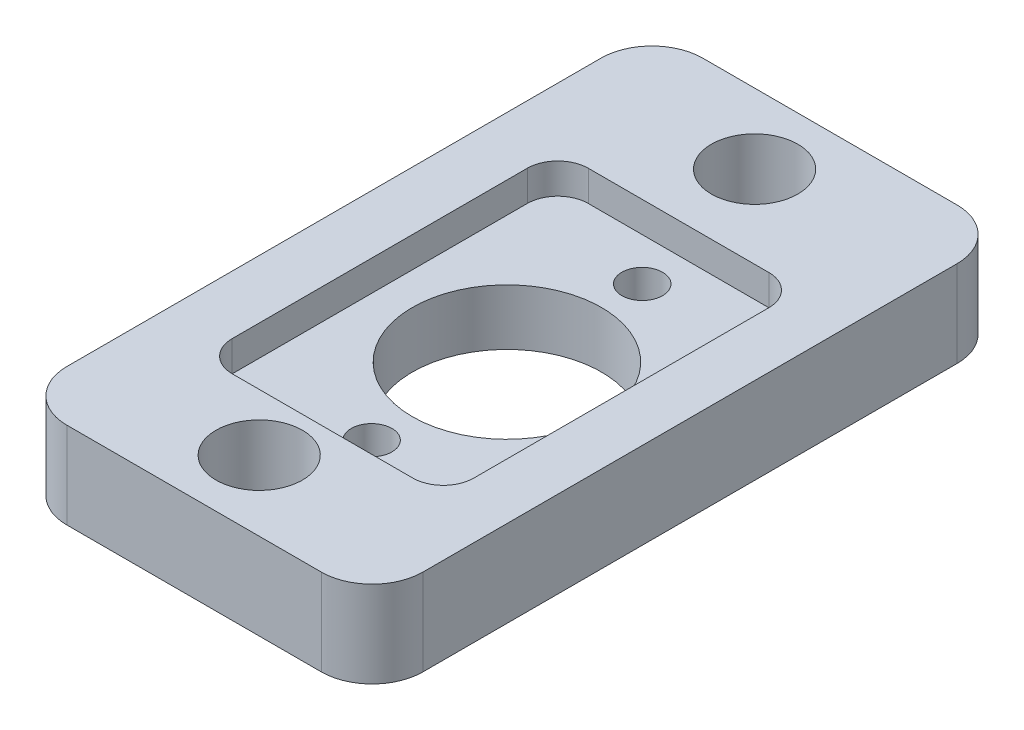
SolidWorks part; units mm, degrees
ref_plane "Front Plane" through (0, 0, 0) normal (0, 0, 1) x (1, 0, 0)
ref_plane "Top Plane" through (0, 0, 0) normal (0, 1, 0) x (1, 0, 0)
ref_plane "Right Plane" through (0, 0, 0) normal (1, 0, 0) x (0, 0, -1)
sketch "Sketch1" plane through (0, 0, 0) normal (0, 1, 0) x (1, 0, 0)
  line L1 (2, 0) -> (12, 0)
  line L2 (0, -2) -> (0, -23)
  line L3 (2, -25) -> (12, -25)
  line L4 (14, -2) -> (14, -23)
  arc A0 (0, -23) -> (2, -25) centre (2, -23) ccw
  arc A1 (12, -25) -> (14, -23) centre (12, -23) ccw
  arc A2 (12, 0) -> (14, -2) centre (12, -2) cw
  arc A3 (2, 0) -> (0, -2) centre (2, -2) ccw
  point P7 (0, -25)
  point P12 (14, 0)
  point P15 (0, 0)
  dimension "D3" = 2
  dimension "D1" = 14
  dimension "D2" = 25
extrude "Boss-Extrude1" add sketch "Sketch1" along normal blind 3.4
sketch "Sketch2" plane through (0, 3.4, 0) normal (0, 1, 0) x (1, 0, 0)
  line L0 (12, 0) -> (2, 0) construction
  line L1 (3.5, -6) -> (10.6, -6)
  line L2 (2.3, -7.2) -> (2.3, -18.8)
  line L3 (3.5, -20) -> (10.6, -20)
  line L4 (11.8, -7.2) -> (11.8, -18.8)
  line L5 (14, -23) -> (14, -2) construction
  arc A0 (2.3, -18.8) -> (3.5, -20) centre (3.5, -18.8) ccw
  arc A1 (10.6, -20) -> (11.8, -18.8) centre (10.6, -18.8) ccw
  arc A2 (10.6, -6) -> (11.8, -7.2) centre (10.6, -7.2) cw
  arc A3 (3.5, -6) -> (2.3, -7.2) centre (3.5, -7.2) ccw
  point P4 (7.05, -6)
  point P9 (2.3, -20)
  point P14 (11.8, -6)
  point P17 (2.3, -6)
  dimension "D4" = 1.2
  dimension "D1" = 9.5
  dimension "D2" = 14
  dimension "D3" = 6
  dimension "D5" = 2.2
extrude "Cut-Extrude1" cut sketch "Sketch2" against normal blind 1.2
sketch "Sketch3" plane through (0, 2.2, 0) normal (0, 1, 0) x (1, 0, 0)
  line L0 (11.8, -18.8) -> (11.8, -7.2) construction
  line L2 (3.5, -20) -> (10.6, -20) construction
  circle A0 centre (7.3, -13) radius 3.72
  circle A1 centre (7.3, -7.68) radius 0.8
  circle A2 centre (7.3, -18.32) radius 0.8
  dimension "D1" = 7.44
  dimension "D4" = 1.6
  dimension "D2" = 4.5
  dimension "D3" = 7
  dimension "D5" = 1.6
extrude "Cut-Extrude2" cut sketch "Sketch3" against normal through all
sketch "Sketch4" plane through (0, 3.4, 0) normal (0, 1, 0) x (1, 0, 0)
  line L0 (0, -12.5) -> (25.4035, -12.5) construction
  line L1 (0, -2) -> (0, -23) construction
  line L2 (12, 0) -> (2, 0) construction
  circle A0 centre (6.8, -2.76) radius 1.7
  circle A2 centre (6.8, -22.24) radius 1.7
  dimension "D1" = 2.76
  dimension "D2" = 6.8
extrude "Cut-Extrude3" cut sketch "Sketch4" against normal through all
